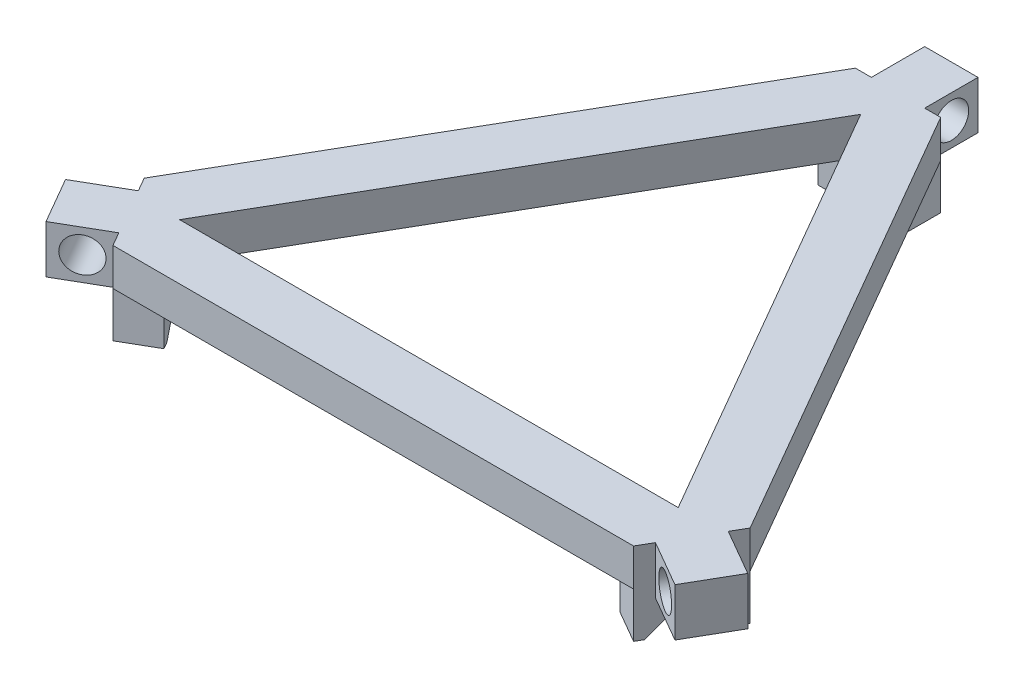
SolidWorks part; units mm, degrees
ref_plane "Front Plane" through (0, 0, 0) normal (0, 0, 1) x (1, 0, 0)
ref_plane "Top Plane" through (0, 0, 0) normal (0, 1, 0) x (1, 0, 0)
ref_plane "Right Plane" through (0, 0, 0) normal (1, 0, 0) x (0, 0, -1)
sketch "Sketch1" plane through (0, 0, 0) normal (0, 1, 0) x (1, 0, 0)
  line L0 (0, 13.716) -> (-11.8784, -6.858)
  line L1 (-11.8784, -6.858) -> (11.8784, -6.858)
  line L2 (11.8784, -6.858) -> (0, 13.716)
  line L3 (-2.032, 15.494) -> (-14.4342, -5.9872)
  line L4 (0, 15.494) -> (2.032, 15.494)
  line L5 (0, 15.494) -> (-2.032, 15.494)
  line L6 (-13.4182, -7.747) -> (-12.4022, -9.5068)
  line L7 (-13.4182, -7.747) -> (-14.4342, -5.9872)
  line L8 (-12.4022, -9.5068) -> (12.4022, -9.5068)
  line L9 (13.4182, -7.747) -> (12.4022, -9.5068)
  line L10 (13.4182, -7.747) -> (14.4342, -5.9872)
  line L11 (2.032, 15.494) -> (14.4342, -5.9872)
extrude "Boss-Extrude1" add sketch "Sketch1" along normal blind 1.778
ref_plane "Plane1" through (0, 0, 0) normal (0, -1, 0) x (-1, 0, 0)
sketch "Sketch3" plane through (0, 0, 0) normal (0, -1, 0) x (-1, 0, 0)
  line L0 (0, 13.716) -> (2.032, 13.716)
  line L1 (0, 13.716) -> (-2.032, 13.716)
  line L2 (2.032, 13.716) -> (2.032, 15.494)
  line L3 (2.032, 15.494) -> (-2.032, 15.494)
  line L4 (-2.032, 15.494) -> (-2.032, 13.716)
extrude "Boss-Extrude2" add sketch "Sketch3" along normal blind 2.159
sketch "Sketch4" plane through (0, 0, -13.716) normal (0, 0, 1) x (1, 0, 0)
  line L0 (0, -0.508) -> (-2.6941, -3.2021)
  line L2 (0, -0.508) -> (2.6941, -3.2021)
  line L4 (-2.6941, -3.2021) -> (2.6941, -3.2021)
extrude "Cut-Extrude1" cut sketch "Sketch4" against normal through all
sketch "Sketch5" plane through (0, 0, 0) normal (0, -1, 0) x (-1, 0, 0)
  circle A0 centre (0, 0) radius 0.254
extrude "Boss-Extrude3" [suppressed] add sketch "Sketch5" against normal blind 1.778 separate body
sketch "Sketch6" plane through (0, 1.778, 0) normal (0, 1, 0) x (1, 0, 0)
  line L0 (0, 15.494) -> (1.27, 15.494)
  line L1 (2.032, 15.494) -> (-2.032, 15.494) construction
  line L2 (0, 15.494) -> (-1.27, 15.494)
  line L3 (-1.27, 15.494) -> (-1.27, 18.034)
  line L4 (-1.27, 18.034) -> (1.27, 18.034)
  line L5 (1.27, 18.034) -> (1.27, 15.494)
extrude "Boss-Extrude4" add sketch "Sketch6" against normal blind 2.286
hole_wizard "#97 (0.0059) Diameter Hole1" positions "Sketch8" profile "Sketch7" hole size "#97" standard "ANSI Inch" end condition through all
sketch "Sketch8" plane through (1.27, 0, 0) normal (1, 0, 0) x (0, 0, -1)
  point P0 (16.764, 0.635)
sketch "Sketch7" plane through (1.27, 0.635, -16.764) normal (0, 1, 0) x (0, 0, -1)
  line L0 (0, 0) -> (0, 18.1579)
  line L1 (0, 18.1579) -> (0.8255, 18.1579)
  line L2 (0.8255, 18.1579) -> (0.8255, 0)
  line L5 (0.8255, 0) -> (0, 0)
  line L11 (0, -6.35) -> (0, 107.95) construction
  dimension "Thru Hole Dia." = 1.651
  dimension "Thru Hole Depth" = 18.1579
pattern_circular "CirPattern2" count 3 every 120 about axis through (0, 0, 0) along (0, 1, 0) of "Boss-Extrude2", "Cut-Extrude1"
pattern_circular "CirPattern3" count 3 every 120 about axis through (0, 0, 0) along (0, 1, 0) of "Boss-Extrude4", "#97 (0.0059) Diameter Hole1"
